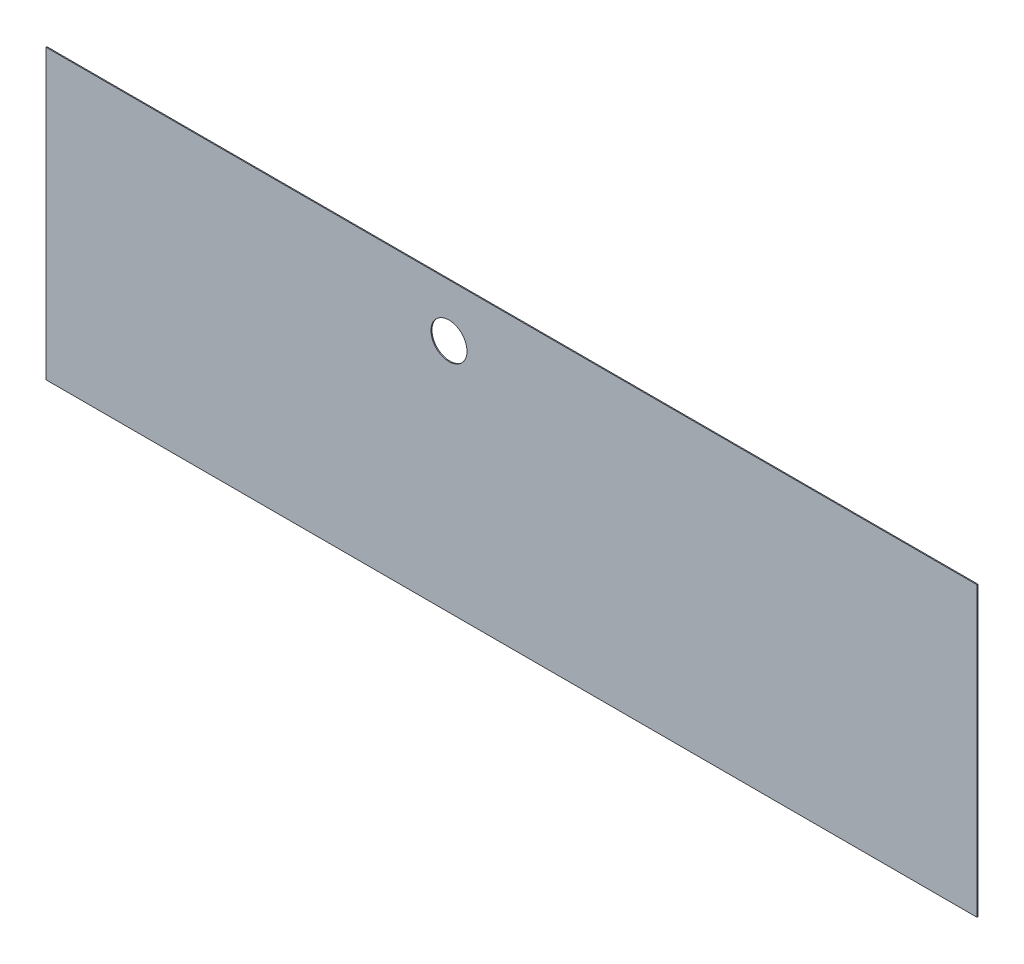
SolidWorks part; units mm, degrees
ref_plane "Alzado" through (0, 0, 0) normal (0, 0, 1) x (1, 0, 0)
ref_plane "Planta" through (0, 0, 0) normal (0, 1, 0) x (1, 0, 0)
ref_plane "Vista lateral" through (0, 0, 0) normal (1, 0, 0) x (0, 0, -1)
sketch "Croquis1" plane through (0, 0, 0) normal (0, 0, 1) x (1, 0, 0)
  line L1 (969.75, -300) -> (-969.75, -300)
  line L2 (969.75, -300) -> (969.75, 300)
  line L3 (969.75, 300) -> (-969.75, 300)
  line L4 (-969.75, -300) -> (-969.75, 300)
  line L5 (969.75, -300) -> (-969.75, 300) construction
  line L6 (969.75, 300) -> (-969.75, -300) construction
  point P0 (0, 0)
  dimension "D1" = 1939.5
  dimension "D2" = 600
extrude "Extruir1" add sketch "Croquis1" along normal blind 2
sketch "Croquis2" plane through (0, 0, 0) normal (0, 0, -1) x (-1, 0, 0)
  line L0 (130.25, 190) -> (-969.75, 190) construction
  line L1 (-969.75, -300) -> (-969.75, 300) construction
  line L2 (130.25, 190) -> (130.25, 300) construction
  line L3 (-969.75, 300) -> (969.75, 300) construction
  circle A0 centre (130.25, 190) radius 37.5
  dimension "D1" = 75
  dimension "D2" = 1100
  dimension "D3" = 110
extrude "Cortar-Extruir1" cut sketch "Croquis2" against normal blind 10
